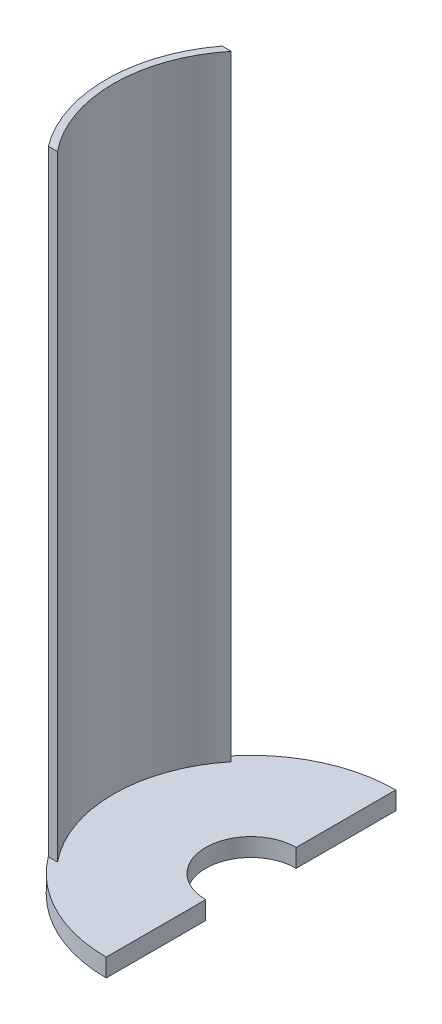
SolidWorks part; units mm, degrees
ref_plane "Front Plane" through (0, 0, 0) normal (0, 0, 1) x (1, 0, 0)
ref_plane "Top Plane" through (0, 0, 0) normal (0, 1, 0) x (1, 0, 0)
ref_plane "Right Plane" through (0, 0, 0) normal (1, 0, 0) x (0, 0, -1)
sketch "Sketch1" plane through (0, 0, 0) normal (0, 1, 0) x (1, 0, 0)
  line L0 (0, 40) -> (0, -40) construction
  line L1 (0, 40) -> (0, 12.5)
  line L2 (0, -12.5) -> (0, -40)
  arc A0 (0, 40) -> (0, -40) centre (0, 0) ccw
  arc A1 (0, 12.5) -> (0, -12.5) centre (0, 0) ccw
  dimension "D1" = 80
  dimension "D2" = 25
extrude "Boss-Extrude1" add sketch "Sketch1" along normal blind 5
sketch "Sketch2" plane through (0, 5, 0) normal (0, 1, 0) x (1, 0, 0)
  line L1 (0, -38) -> (0, -40)
  line L2 (-29.4618, 24) -> (-32, 24)
  line L4 (-29.4618, -24) -> (-32, -24)
  arc A0 (0, 40) -> (0, -40) centre (0, 0) ccw construction
  arc A1 (-32, 24) -> (-32, -24) centre (0, 0) ccw
  arc A2 (-29.4618, 24) -> (-29.4618, -24) centre (0, 0) ccw
  arc A3 (0, 40) -> (0, -40) centre (0, 0) ccw construction
  arc A4 (0, 38) -> (0, -38) centre (0, 0) ccw construction
  point P11 (0, 0)
  arc M7 (0, 40) -> (0, -40) centre (0, 0) ccw
  dimension "D2" = 24
  dimension "D3" = 24
  dimension "D1" = 2
extrude "Boss-Extrude2" add sketch "Sketch2" along normal blind 170 contours A2 L2 L4 M7
